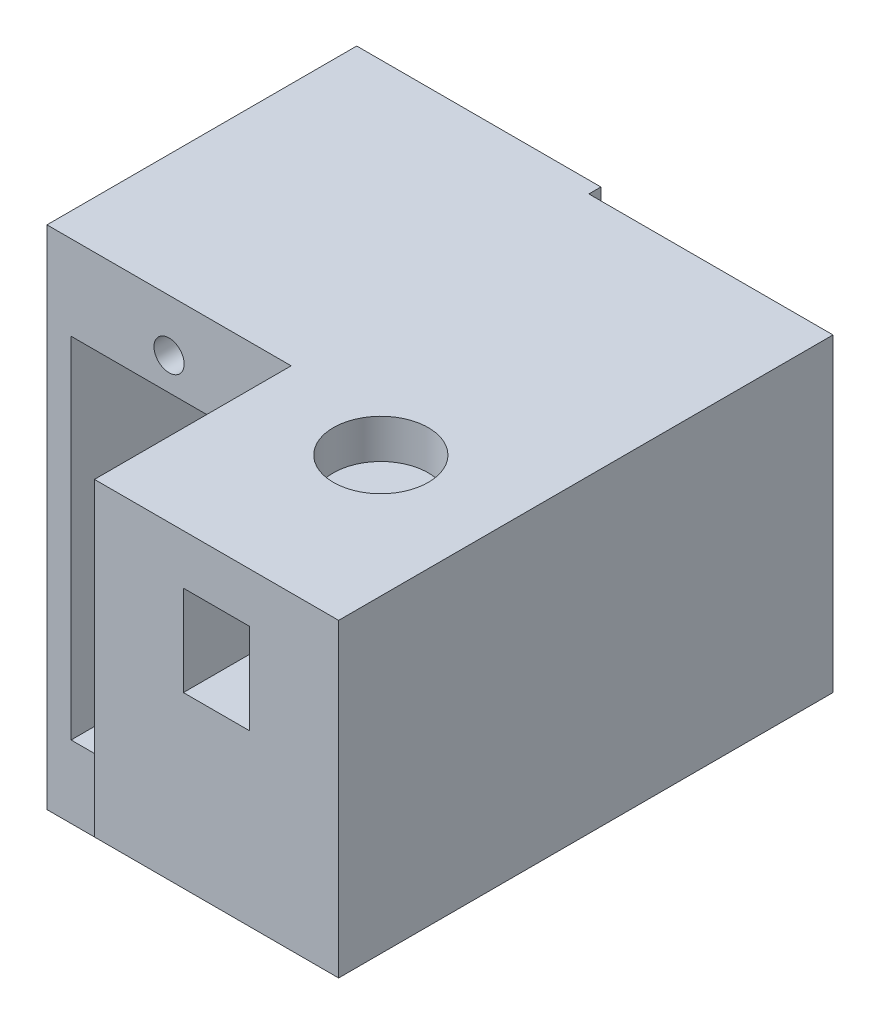
SolidWorks part; units mm, degrees
material "ABS"
ref_plane "Front Plane" through (0, 0, 0) normal (0, 0, 1) x (1, 0, 0)
ref_plane "Top Plane" through (0, 0, 0) normal (0, 1, 0) x (1, 0, 0)
ref_plane "Right Plane" through (0, 0, 0) normal (1, 0, 0) x (0, 0, -1)
sketch "Sketch1" plane through (0, 0, 0) normal (0, 1, 0) x (1, 0, 0)
  line L1 (-8.1, -10.9) -> (8.1, -10.9)
  line L2 (-8.1, -10.9) -> (-8.1, 21.9)
  line L3 (-8.1, 21.9) -> (8.1, 21.9)
  line L4 (8.1, -10.9) -> (8.1, 21.9)
extrude "Boss-Extrude1" add sketch "Sketch1" along normal mid plane 20.55 from offset 17.075
sketch "Sketch2" plane through (0, 0, 0) normal (0, 0, 1) x (1, 0, 0)
  line L0 (-8.1, -6.8) -> (-8.1, -27.35) construction
  line L1 (-24.3, -40.4) -> (-8.1, -40.4)
  line L2 (-24.3, -40.4) -> (-24.3, -7.6)
  line L3 (-24.3, -7.6) -> (-8.1, -7.6)
  line L4 (-8.1, -40.4) -> (-8.1, -7.6)
extrude "Boss-Extrude2" add sketch "Sketch2" along normal mid plane 20.55 from offset 12.425
sketch "Sketch3" plane through (0, 0, 0) normal (0, 1, 0) x (1, 0, 0)
  line L1 (-24.3, 2.15) -> (-8.1, 2.15)
  line L2 (-24.3, 2.15) -> (-24.3, 22.7)
  line L3 (-24.3, 22.7) -> (-8.1, 22.7)
  line L4 (-8.1, 2.15) -> (-8.1, 22.7)
extrude "Boss-Extrude3" add sketch "Sketch3" along normal mid plane 1 from offset 7.3
sketch "Sketch4" plane through (0, 0, 0) normal (0, 1, 0) x (1, 0, 0)
  line L1 (-6.5, -6.1) -> (6.5, -6.1)
  line L2 (-6.5, -6.1) -> (-6.5, 17.1)
  line L3 (-6.5, 17.1) -> (6.5, 17.1)
  line L4 (6.5, -6.1) -> (6.5, 17.1)
extrude "Cut-Extrude1" cut sketch "Sketch4" against normal mid plane 17.25 from offset 18.725
sketch "Sketch5" plane through (0, 0, 0) normal (0, 1, 0) x (1, 0, 0)
  circle A0 centre (0, 19.25) radius 1
extrude "Cut-Extrude2" cut sketch "Sketch5" against normal mid plane 6 from offset 24.35
sketch "Sketch6" plane through (0, 0, 0) normal (0, 1, 0) x (1, 0, 0)
  circle A0 centre (0, -8.25) radius 1
extrude "Cut-Extrude3" cut sketch "Sketch6" against normal mid plane 6 from offset 24.35
sketch "Sketch7" plane through (0, 0, 0) normal (0, 1, 0) x (1, 0, 0)
  circle A0 centre (0, 0) radius 3.15
extrude "Cut-Extrude4" cut sketch "Sketch7" against normal mid plane 2.6 from offset 8.1
sketch "Sketch8" plane through (0, 0, 0) normal (0, 0, 1) x (1, 0, 0)
  line L1 (-2.2, -16.1) -> (2.2, -16.1)
  line L2 (-2.2, -16.1) -> (-2.2, -10.1)
  line L3 (-2.2, -10.1) -> (2.2, -10.1)
  line L4 (2.2, -16.1) -> (2.2, -10.1)
extrude "Cut-Extrude5" cut sketch "Sketch8" against normal mid plane 4.8 from offset 8.5
sketch "Sketch9" plane through (0, 0, 0) normal (0, 0, 1) x (1, 0, 0)
  line L1 (-22.7, -35.6) -> (-9.7, -35.6)
  line L2 (-22.7, -35.6) -> (-22.7, -12.4)
  line L3 (-22.7, -12.4) -> (-9.7, -12.4)
  line L4 (-9.7, -35.6) -> (-9.7, -12.4)
extrude "Cut-Extrude6" cut sketch "Sketch9" against normal mid plane 17.25 from offset 10.775
sketch "Sketch10" plane through (0, 0, 0) normal (0, 0, 1) x (1, 0, 0)
  circle A0 centre (-16.2, -37.75) radius 1
extrude "Cut-Extrude7" cut sketch "Sketch10" against normal mid plane 6 from offset 5.15
sketch "Sketch11" plane through (0, 0, 0) normal (0, 0, 1) x (1, 0, 0)
  circle A0 centre (-16.2, -10.25) radius 1
extrude "Cut-Extrude8" cut sketch "Sketch11" against normal mid plane 6 from offset 5.15
sketch "Sketch12" plane through (0, 0, 0) normal (0, 0, 1) x (1, 0, 0)
  circle A0 centre (-16.2, -18.5) radius 3.15
extrude "Cut-Extrude9" cut sketch "Sketch12" against normal mid plane 2.6 from offset 21.4
sketch "Sketch13" plane through (0, 0, 0) normal (0, 1, 0) x (1, 0, 0)
  line L1 (-18.4, 13.4) -> (-14, 13.4)
  line L2 (-18.4, 13.4) -> (-18.4, 19.4)
  line L3 (-18.4, 19.4) -> (-14, 19.4)
  line L4 (-14, 13.4) -> (-14, 19.4)
extrude "Cut-Extrude10" cut sketch "Sketch13" against normal mid plane 4.8 from offset 10
